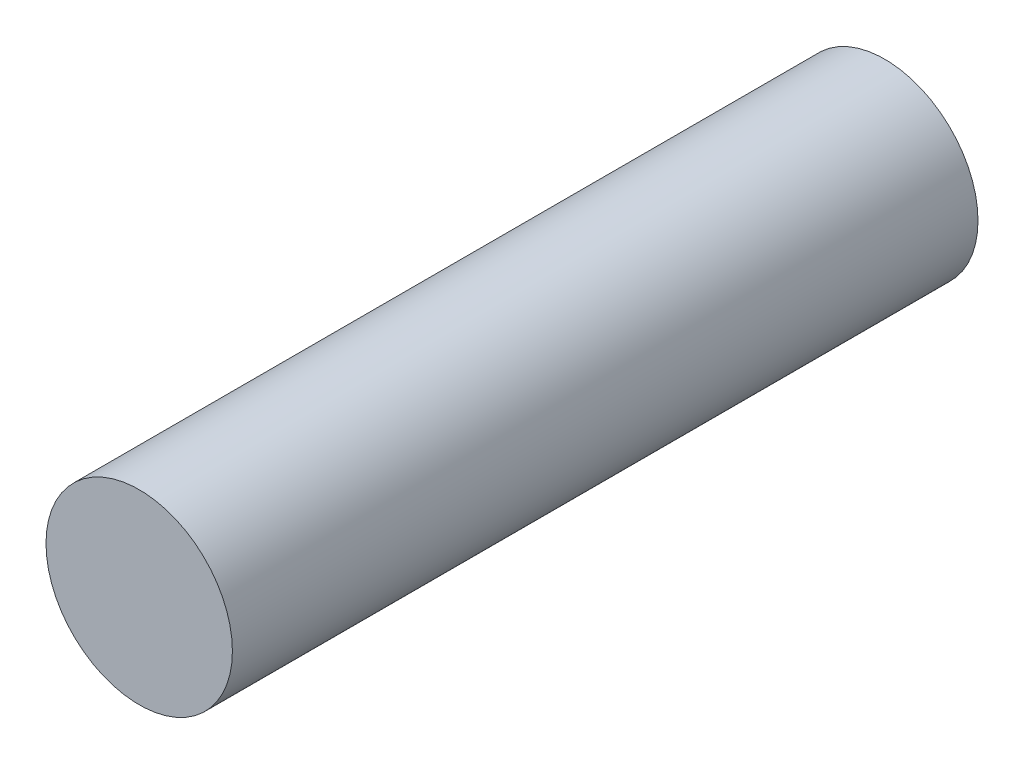
SolidWorks part; units mm, degrees
ref_plane "Front Plane" through (0, 0, 0) normal (0, 0, 1) x (1, 0, 0)
ref_plane "Top Plane" through (0, 0, 0) normal (0, 1, 0) x (1, 0, 0)
ref_plane "Right Plane" through (0, 0, 0) normal (1, 0, 0) x (0, 0, -1)
sketch "Sketch1" plane through (0, 0, 0) normal (0, 0, 1) x (1, 0, 0)
  circle A0 centre (0, 0) radius 12.5
extrude "Boss-Extrude1" add sketch "Sketch1" along normal blind 100
